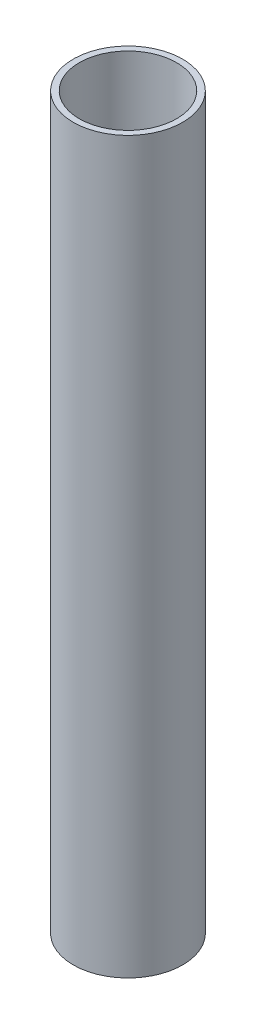
SolidWorks part; units mm, degrees
ref_plane "Front Plane" through (0, 0, 0) normal (0, 0, 1) x (1, 0, 0)
ref_plane "Top Plane" through (0, 0, 0) normal (0, 1, 0) x (1, 0, 0)
ref_plane "Right Plane" through (0, 0, 0) normal (1, 0, 0) x (0, 0, -1)
sketch "Sketch1" plane through (0, 0, 0) normal (0, 1, 0) x (1, 0, 0)
  circle A0 centre (0, 0) radius 40
  circle A1 centre (0, 0) radius 45
  dimension "D1" = 5
extrude "Boss-Extrude1" add sketch "Sketch1" along normal blind 600
